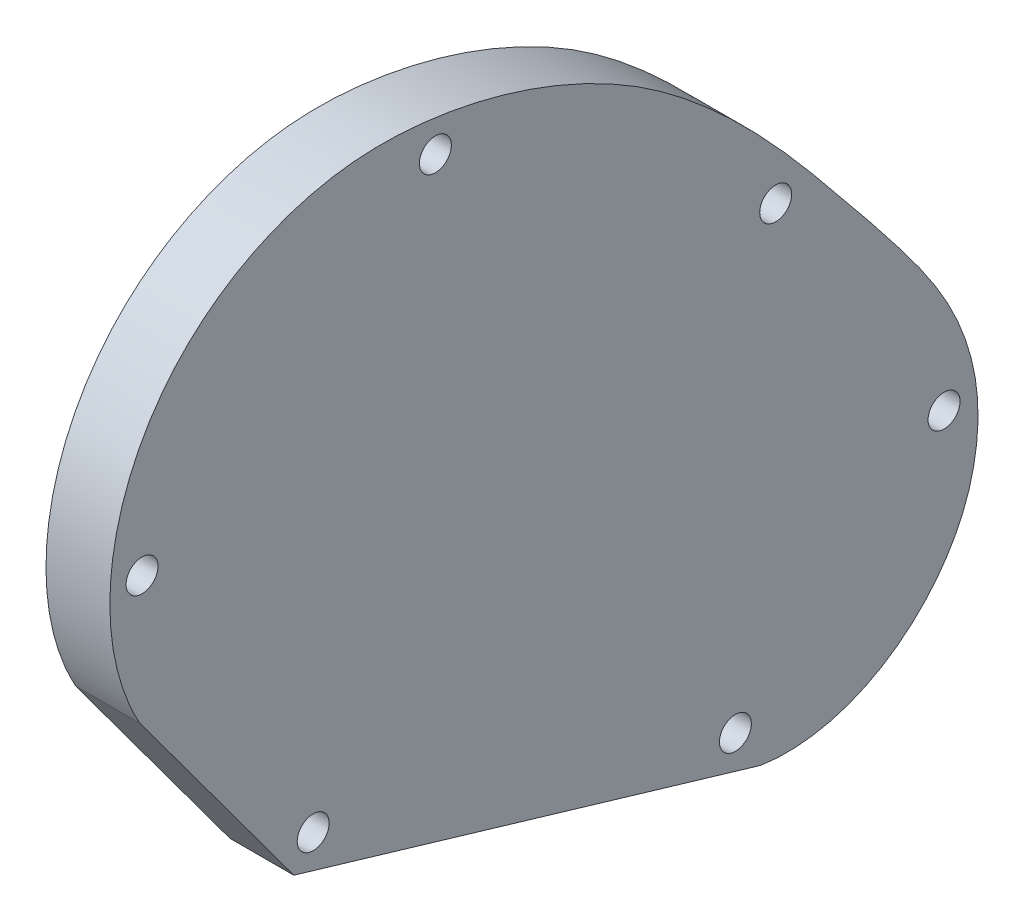
SolidWorks part; units mm, degrees
ref_plane "Front Plane" through (0, 0, 0) normal (0, 0, 1) x (1, 0, 0)
ref_plane "Top Plane" through (0, 0, 0) normal (0, 1, 0) x (1, 0, 0)
ref_plane "Right Plane" through (0, 0, 0) normal (1, 0, 0) x (0, 0, -1)
sketch "Sketch3" plane through (0, 0, 0) normal (1, 0, 0) x (0, 0, -1)
  line L0 (-47.4417, 27.8421) -> (-35.1817, 11.2313)
  line L1 (-35.1817, 11.2313) -> (1.9496, 0.2335)
  spline S0 degree 3 poles (1.9496, 0.2335) (4.8903, -0.232) (10.1601, 0.7351) (15.612, 5.1491) (18.8844, 10.6471) (19.674, 17.2412) (17.4406, 24.2162) (13.2326, 30.1292) (8.5514, 35.8985) (3.8276, 41.6659) (-1.3708, 47.0272) (-7.2612, 51.797) (-14.7784, 55.6982) (-22.952, 57.9925) (-31.9743, 58.3344) (-39.4706, 55.7107) (-45.2724, 50.7737) (-48.7598, 44.894) (-50.4301, 36.8093) (-49.1683, 30.9466) (-47.4417, 27.8421) knots 0 0 0 0 0.064656 0.112182 0.149246 0.202687 0.251879 0.306377 0.360714 0.414933 0.469634 0.524172 0.580244 0.654106 0.708421 0.775975 0.822312 0.872984 0.922834 1 1 1 1
extrude "Boss-Extrude1" add sketch "Sketch3" along normal blind 5.08
sketch "Sketch4" plane through (0, 0, 0) normal (-1, 0, 0) x (0, 0, 1)
  line L0 (35.1817, 11.2313) -> (-1.9496, 0.2335) construction
  line L1 (47.4417, 27.8421) -> (35.1817, 11.2313) construction
  circle A0 centre (33.6438, 13.4249) radius 1.27
  circle A1 centre (47.2527, 37.9218) radius 1.27
  circle A2 centre (23.9254, 55.2563) radius 1.27
  circle A3 centre (-3.1381, 38.3448) radius 1.27
  circle A4 centre (-16.5259, 17.3754) radius 1.27
  circle A5 centre (0.067, 3.4798) radius 1.27
  point P12 (0, 3.7061)
  point P14 (-16.5259, 17.3754)
  point P18 (23.913, 55.5277)
  point P19 (23.9254, 55.2563)
  point P20 (0, 0)
  point P21 (47.2527, 37.9218)
  point P24 (-3.1381, 38.3448)
  dimension "D1" = 2.54
  dimension "D2" = 2.54
  dimension "D3" = 2.54
  dimension "D4" = 2.54
  dimension "D5" = 2.54
  dimension "D6" = 2.54
  dimension "D7" = 2.54
  dimension "D8" = 2.54
  dimension "D9" = 2.54
extrude "Cut-Extrude1" cut sketch "Sketch4" against normal blind 5.08
